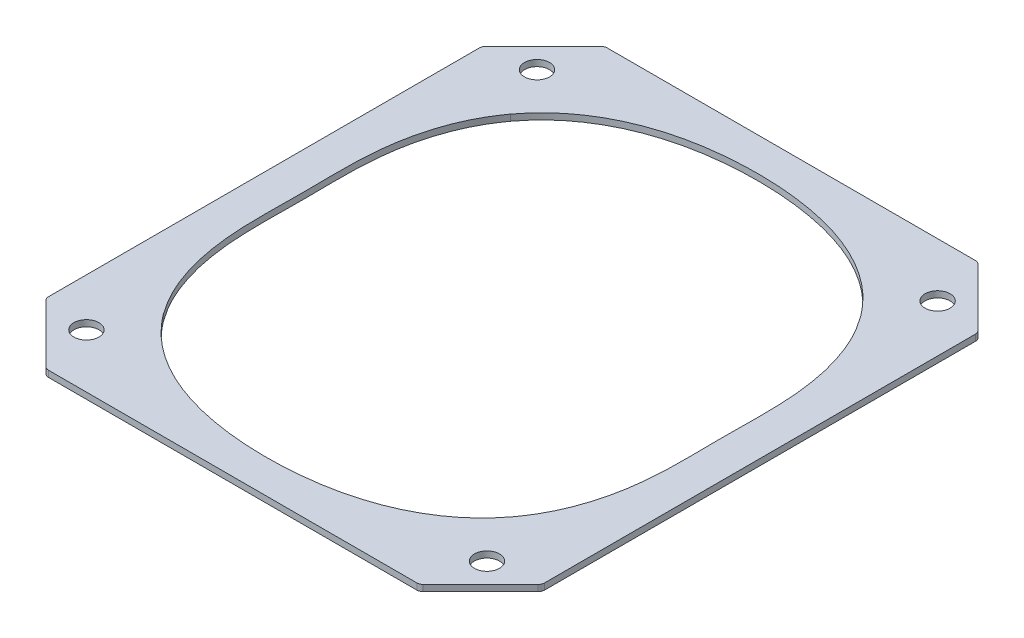
SolidWorks part; units mm, degrees
ref_plane "前视基准面" through (0, 0, 0) normal (0, 0, 1) x (1, 0, 0)
ref_plane "上视基准面" through (0, 0, 0) normal (0, 1, 0) x (1, 0, 0)
ref_plane "右视基准面" through (0, 0, 0) normal (1, 0, 0) x (0, 0, -1)
sketch "草图1" plane through (0, -17.7989, 0) normal (0, -1, 0) x (1, 0, 0)
  line L8 (-395.7062, -91.9037) -> (-395.7062, -160.7573)
  line L9 (-395.4134, -161.4643) -> (-386.224, -170.6537)
  line L10 (-385.517, -170.9465) -> (-326.6634, -170.9465)
  line L11 (-325.9564, -170.6537) -> (-316.7671, -161.4643)
  line L12 (-316.4742, -160.7573) -> (-316.4742, -91.9037)
  line L13 (-316.7671, -91.1967) -> (-325.9564, -82.0074)
  line L14 (-326.6634, -81.7145) -> (-385.517, -81.7145)
  line L15 (-386.224, -82.0074) -> (-395.4134, -91.1967)
  line L16 (-395.7062, -91.9037) -> (-395.7062, -160.7573)
  line L17 (-395.4134, -161.4643) -> (-386.224, -170.6537)
  line L18 (-385.517, -170.9465) -> (-326.6634, -170.9465)
  line L19 (-325.9564, -170.6537) -> (-316.7671, -161.4643)
  line L20 (-316.4742, -160.7573) -> (-316.4742, -91.9037)
  line L21 (-316.7671, -91.1967) -> (-325.9564, -82.0074)
  line L22 (-326.6634, -81.7145) -> (-385.517, -81.7145)
  line L23 (-386.224, -82.0074) -> (-395.4134, -91.1967)
  circle A0 centre (-388.0902, -90.3305) radius 2
  circle A1 centre (-324.0902, -90.3305) radius 2
  circle A2 centre (-324.0902, -162.3305) radius 2
  circle A3 centre (-388.0902, -162.3305) radius 2
  arc A8 (-395.4134, -91.1967) -> (-395.7062, -91.9037) centre (-394.7064, -91.9037) ccw
  arc A9 (-395.7062, -160.7573) -> (-395.4134, -161.4643) centre (-394.7064, -160.7573) ccw
  arc A10 (-386.224, -170.6537) -> (-385.517, -170.9465) centre (-385.517, -169.9467) ccw
  arc A11 (-326.6634, -170.9465) -> (-325.9564, -170.6537) centre (-326.6634, -169.9467) ccw
  arc A12 (-316.7671, -161.4643) -> (-316.4742, -160.7573) centre (-317.4741, -160.7573) ccw
  arc A13 (-316.4742, -91.9037) -> (-316.7671, -91.1967) centre (-317.4741, -91.9037) ccw
  arc A14 (-325.9564, -82.0074) -> (-326.6634, -81.7145) centre (-326.6634, -82.7144) ccw
  arc A15 (-385.517, -81.7145) -> (-386.224, -82.0074) centre (-385.517, -82.7144) ccw
  arc A16 (-395.4134, -91.1967) -> (-395.7062, -91.9037) centre (-394.7064, -91.9037) ccw
  arc A17 (-395.7062, -160.7573) -> (-395.4134, -161.4643) centre (-394.7064, -160.7573) ccw
  arc A18 (-386.224, -170.6537) -> (-385.517, -170.9465) centre (-385.517, -169.9467) ccw
  arc A19 (-326.6634, -170.9465) -> (-325.9564, -170.6537) centre (-326.6634, -169.9467) ccw
  arc A20 (-316.7671, -161.4643) -> (-316.4742, -160.7573) centre (-317.4741, -160.7573) ccw
  arc A21 (-316.4742, -91.9037) -> (-316.7671, -91.1967) centre (-317.4741, -91.9037) ccw
  arc A22 (-325.9564, -82.0074) -> (-326.6634, -81.7145) centre (-326.6634, -82.7144) ccw
  arc A23 (-385.517, -81.7145) -> (-386.224, -82.0074) centre (-385.517, -82.7144) ccw
  spline S0 degree 3 poles (2764.3146, -2688.1904) (-361.7131, -9.7083) (-300.2988, -122.2786) (-329.8062, -156.114) (-330.2605, -156.597) (-331.2134, -157.5207) (-331.7079, -157.9558) (-332.7233, -158.787) (-333.2443, -159.1831) (-334.8489, -160.3094) (-335.9724, -160.9808) (-337.7313, -161.8788) (-338.3323, -162.1611) (-339.5415, -162.6834) (-340.1506, -162.9241) (-343.2165, -164.0348) (-345.7331, -164.631) (-349.5749, -165.2203) (-350.8669, -165.3649) (-353.4729, -165.5531) (-354.79, -165.5964) (-358.7129, -165.5924) (-361.3089, -165.4142) (-365.1679, -164.8303) (-366.4484, -164.5823) (-368.3581, -164.1099) (-368.9945, -163.9352) (-370.2542, -163.552) (-370.8767, -163.3438) (-372.7217, -162.6682) (-373.9218, -162.1503) (-375.6695, -161.2547) (-376.2432, -160.9362) (-377.3716, -160.2561) (-377.9264, -159.8942) (-378.9981, -159.1367) (-379.5172, -158.7399) (-380.5236, -157.9118) (-381.0107, -157.4804) (-381.9433, -156.5723) (-382.3898, -156.0968) (-411.9601, -122.1457) (-358.609, 0.6771) (-3190.2029, -3001.8405) knots -2.056753 -2.056753 -2.056753 -2.056753 0.03125 0.03125 0.0625 0.0625 0.09375 0.09375 0.125 0.125 0.1875 0.1875 0.21875 0.21875 0.25 0.25 0.375 0.375 0.4375 0.4375 0.5 0.5 0.625 0.625 0.6875 0.6875 0.71875 0.71875 0.75 0.75 0.8125 0.8125 0.84375 0.84375 0.875 0.875 0.90625 0.90625 0.9375 0.9375 0.96875 0.96875 3.087281 3.087281 3.087281 3.087281 only from (-328.1155, -154.0747) to (-384.0649, -154.0747) construction
  spline S1 degree 3 poles (3066.8349, 2011.7596) (-541.7707, -102.2534) (-351.5553, -55.0595) (-325.8879, -102.1729) (-325.621, -102.7145) (-325.1212, -103.817) (-324.8887, -104.3785) (-323.8209, -107.1997) (-323.2412, -109.5222) (-322.6978, -113.0838) (-322.569, -114.2867) (-322.3992, -116.6958) (-322.3584, -117.9009) (-322.329, -120.3119) (-322.341, -121.5178) (-322.3692, -123.9295) (-322.384, -125.1354) (-322.3839, -127.5468) (-322.3689, -128.7522) (-322.3408, -131.1632) (-322.329, -132.3687) (-322.3588, -134.7743) (-322.3998, -135.9747) (-322.5686, -138.3671) (-322.6956, -139.5592) (-323.0566, -141.9331) (-323.2915, -143.1149) (-323.7444, -144.878) (-323.9117, -145.4633) (-324.2757, -146.6159) (-324.4728, -147.1851) (-324.8991, -148.3083) (-325.129, -148.8621) (-325.6242, -149.9528) (-325.889, -150.49) (-351.705, -197.8838) (-552.0003, -162.2575) (3217.366, -2000.3926) knots -2.687586 -2.687586 -2.687586 -2.687586 0.0625 0.0625 0.09375 0.09375 0.125 0.125 0.25 0.25 0.3125 0.3125 0.375 0.375 0.4375 0.4375 0.5 0.5 0.5625 0.5625 0.625 0.625 0.6875 0.6875 0.75 0.75 0.8125 0.8125 0.84375 0.84375 0.875 0.875 0.90625 0.90625 0.9375 0.9375 3.717731 3.717731 3.717731 3.717731 only from (-328.1155, -98.5863) to (-328.1155, -154.0747) construction
  spline S2 degree 3 poles (-3476.4951, 2435.5294) (-350.4673, -242.9527) (-411.8817, -130.3824) (-382.3743, -96.547) (-381.92, -96.0641) (-380.9671, -95.1403) (-380.4725, -94.7052) (-379.4571, -93.874) (-378.9361, -93.478) (-377.3315, -92.3517) (-376.208, -91.6802) (-374.4491, -90.7822) (-373.8482, -90.5) (-372.6389, -89.9776) (-372.0298, -89.7369) (-368.964, -88.6262) (-366.4473, -88.03) (-362.6055, -87.4408) (-361.3135, -87.2962) (-358.7076, -87.1079) (-357.3904, -87.0646) (-353.4675, -87.0687) (-350.8716, -87.2469) (-347.0125, -87.8308) (-345.732, -88.0788) (-343.8223, -88.5511) (-343.1859, -88.7258) (-341.9262, -89.1091) (-341.3037, -89.3172) (-339.4587, -89.9929) (-338.2586, -90.5107) (-336.5109, -91.4064) (-335.9372, -91.7249) (-334.8088, -92.4049) (-334.254, -92.7669) (-333.1824, -93.5243) (-332.6633, -93.9211) (-331.6568, -94.7492) (-331.1697, -95.1807) (-330.2371, -96.0888) (-329.7906, -96.5642) (-300.2204, -130.5153) (-353.5714, -253.3381) (2478.0225, 2749.1795) knots -2.056753 -2.056753 -2.056753 -2.056753 0.03125 0.03125 0.0625 0.0625 0.09375 0.09375 0.125 0.125 0.1875 0.1875 0.21875 0.21875 0.25 0.25 0.375 0.375 0.4375 0.4375 0.5 0.5 0.625 0.625 0.6875 0.6875 0.71875 0.71875 0.75 0.75 0.8125 0.8125 0.84375 0.84375 0.875 0.875 0.90625 0.90625 0.9375 0.9375 0.96875 0.96875 3.087281 3.087281 3.087281 3.087281 only from (-384.0649, -98.5863) to (-328.1155, -98.5863) construction
  spline S3 degree 3 poles (-3779.0153, -2264.4206) (-170.4097, -150.4076) (-360.6252, -197.6015) (-386.2925, -150.4881) (-386.5595, -149.9466) (-387.0593, -148.8441) (-387.2917, -148.2825) (-388.3595, -145.4613) (-388.9393, -143.1389) (-389.4827, -139.5773) (-389.6114, -138.3743) (-389.7813, -135.9652) (-389.822, -134.7601) (-389.8515, -132.3491) (-389.8394, -131.1433) (-389.8113, -128.7315) (-389.7964, -127.5257) (-389.7966, -125.1143) (-389.8115, -123.9088) (-389.8396, -121.4978) (-389.8515, -120.2924) (-389.8216, -117.8867) (-389.7806, -116.6864) (-389.6119, -114.294) (-389.4848, -113.1019) (-389.1238, -110.7279) (-388.8889, -109.5461) (-388.436, -107.783) (-388.2687, -107.1978) (-387.9048, -106.0451) (-387.7077, -105.4759) (-387.2813, -104.3527) (-387.0514, -103.799) (-386.5563, -102.7082) (-386.2914, -102.171) (-360.4754, -54.7773) (-160.1801, -90.4035) (-3929.5465, 1747.7316) knots -2.687586 -2.687586 -2.687586 -2.687586 0.0625 0.0625 0.09375 0.09375 0.125 0.125 0.25 0.25 0.3125 0.3125 0.375 0.375 0.4375 0.4375 0.5 0.5 0.5625 0.5625 0.625 0.625 0.6875 0.6875 0.75 0.75 0.8125 0.8125 0.84375 0.84375 0.875 0.875 0.90625 0.90625 0.9375 0.9375 3.717731 3.717731 3.717731 3.717731 only from (-384.0649, -154.0747) to (-384.0649, -98.5863) construction
  spline S4 degree 3 poles (-328.1155, -154.0747) (-328.5211, -154.5995) (-328.936, -155.1162) (-329.8062, -156.114) (-330.2605, -156.597) (-331.2134, -157.5207) (-331.7079, -157.9558) (-332.7233, -158.787) (-333.2443, -159.1831) (-334.8489, -160.3094) (-335.9724, -160.9808) (-337.7313, -161.8788) (-338.3323, -162.1611) (-339.5415, -162.6834) (-340.1506, -162.9241) (-343.2165, -164.0348) (-345.7331, -164.631) (-349.5749, -165.2203) (-350.8669, -165.3649) (-353.4729, -165.5531) (-354.79, -165.5964) (-358.7129, -165.5924) (-361.3089, -165.4142) (-365.1679, -164.8303) (-366.4484, -164.5823) (-368.3581, -164.1099) (-368.9945, -163.9352) (-370.2542, -163.552) (-370.8767, -163.3438) (-372.7217, -162.6682) (-373.9218, -162.1503) (-375.6695, -161.2547) (-376.2432, -160.9362) (-377.3716, -160.2561) (-377.9264, -159.8942) (-378.9981, -159.1367) (-379.5172, -158.7399) (-380.5236, -157.9118) (-381.0107, -157.4804) (-381.9433, -156.5723) (-382.3898, -156.0968) (-383.2495, -155.1098) (-383.6614, -154.5968) (-384.0649, -154.0747) knots 0 0 0 0 0.03125 0.03125 0.0625 0.0625 0.09375 0.09375 0.125 0.125 0.1875 0.1875 0.21875 0.21875 0.25 0.25 0.375 0.375 0.4375 0.4375 0.5 0.5 0.625 0.625 0.6875 0.6875 0.71875 0.71875 0.75 0.75 0.8125 0.8125 0.84375 0.84375 0.875 0.875 0.90625 0.90625 0.9375 0.9375 0.96875 0.96875 1 1 1 1
  spline S5 degree 3 poles (-328.1155, -98.5863) (-327.415, -99.5746) (-326.7531, -100.5849) (-325.8879, -102.1729) (-325.621, -102.7145) (-325.1212, -103.817) (-324.8887, -104.3785) (-323.8209, -107.1997) (-323.2412, -109.5222) (-322.6978, -113.0838) (-322.569, -114.2867) (-322.3992, -116.6958) (-322.3584, -117.9009) (-322.329, -120.3119) (-322.341, -121.5178) (-322.3692, -123.9295) (-322.384, -125.1354) (-322.3839, -127.5468) (-322.3689, -128.7522) (-322.3408, -131.1632) (-322.329, -132.3687) (-322.3588, -134.7743) (-322.3998, -135.9747) (-322.5686, -138.3671) (-322.6956, -139.5592) (-323.0566, -141.9331) (-323.2915, -143.1149) (-323.7444, -144.878) (-323.9117, -145.4633) (-324.2757, -146.6159) (-324.4728, -147.1851) (-324.8991, -148.3083) (-325.129, -148.8621) (-325.6242, -149.9528) (-325.889, -150.49) (-326.7499, -152.0704) (-327.4121, -153.0823) (-328.1155, -154.0747) knots 0 0 0 0 0.0625 0.0625 0.09375 0.09375 0.125 0.125 0.25 0.25 0.3125 0.3125 0.375 0.375 0.4375 0.4375 0.5 0.5 0.5625 0.5625 0.625 0.625 0.6875 0.6875 0.75 0.75 0.8125 0.8125 0.84375 0.84375 0.875 0.875 0.90625 0.90625 0.9375 0.9375 1 1 1 1
  spline S6 degree 3 poles (-384.0649, -98.5863) (-383.6593, -98.0615) (-383.2445, -97.5449) (-382.3743, -96.547) (-381.92, -96.0641) (-380.9671, -95.1403) (-380.4725, -94.7052) (-379.4571, -93.874) (-378.9361, -93.478) (-377.3315, -92.3517) (-376.208, -91.6802) (-374.4491, -90.7822) (-373.8482, -90.5) (-372.6389, -89.9776) (-372.0298, -89.7369) (-368.964, -88.6262) (-366.4473, -88.03) (-362.6055, -87.4408) (-361.3135, -87.2962) (-358.7076, -87.1079) (-357.3904, -87.0646) (-353.4675, -87.0687) (-350.8716, -87.2469) (-347.0125, -87.8308) (-345.732, -88.0788) (-343.8223, -88.5511) (-343.1859, -88.7258) (-341.9262, -89.1091) (-341.3037, -89.3172) (-339.4587, -89.9929) (-338.2586, -90.5107) (-336.5109, -91.4064) (-335.9372, -91.7249) (-334.8088, -92.4049) (-334.254, -92.7669) (-333.1824, -93.5243) (-332.6633, -93.9211) (-331.6568, -94.7492) (-331.1697, -95.1807) (-330.2371, -96.0888) (-329.7906, -96.5642) (-328.9309, -97.5513) (-328.519, -98.0642) (-328.1155, -98.5863) knots 0 0 0 0 0.03125 0.03125 0.0625 0.0625 0.09375 0.09375 0.125 0.125 0.1875 0.1875 0.21875 0.21875 0.25 0.25 0.375 0.375 0.4375 0.4375 0.5 0.5 0.625 0.625 0.6875 0.6875 0.71875 0.71875 0.75 0.75 0.8125 0.8125 0.84375 0.84375 0.875 0.875 0.90625 0.90625 0.9375 0.9375 0.96875 0.96875 1 1 1 1
  spline S7 degree 3 poles (-384.0649, -154.0747) (-384.7654, -153.0864) (-385.4273, -152.0762) (-386.2925, -150.4881) (-386.5595, -149.9466) (-387.0593, -148.8441) (-387.2917, -148.2825) (-388.3595, -145.4613) (-388.9393, -143.1389) (-389.4827, -139.5773) (-389.6114, -138.3743) (-389.7813, -135.9652) (-389.822, -134.7601) (-389.8515, -132.3491) (-389.8394, -131.1433) (-389.8113, -128.7315) (-389.7964, -127.5257) (-389.7966, -125.1143) (-389.8115, -123.9088) (-389.8396, -121.4978) (-389.8515, -120.2924) (-389.8216, -117.8867) (-389.7806, -116.6864) (-389.6119, -114.294) (-389.4848, -113.1019) (-389.1238, -110.7279) (-388.8889, -109.5461) (-388.436, -107.783) (-388.2687, -107.1978) (-387.9048, -106.0451) (-387.7077, -105.4759) (-387.2813, -104.3527) (-387.0514, -103.799) (-386.5563, -102.7082) (-386.2914, -102.171) (-385.4306, -100.5907) (-384.7683, -99.5788) (-384.0649, -98.5863) knots 0 0 0 0 0.0625 0.0625 0.09375 0.09375 0.125 0.125 0.25 0.25 0.3125 0.3125 0.375 0.375 0.4375 0.4375 0.5 0.5 0.5625 0.5625 0.625 0.625 0.6875 0.6875 0.75 0.75 0.8125 0.8125 0.84375 0.84375 0.875 0.875 0.90625 0.90625 0.9375 0.9375 1 1 1 1
  dimension "D2" = 4
  dimension "D1" = 0
extrude "凸台-拉伸1" add sketch "草图1" along normal blind 1
